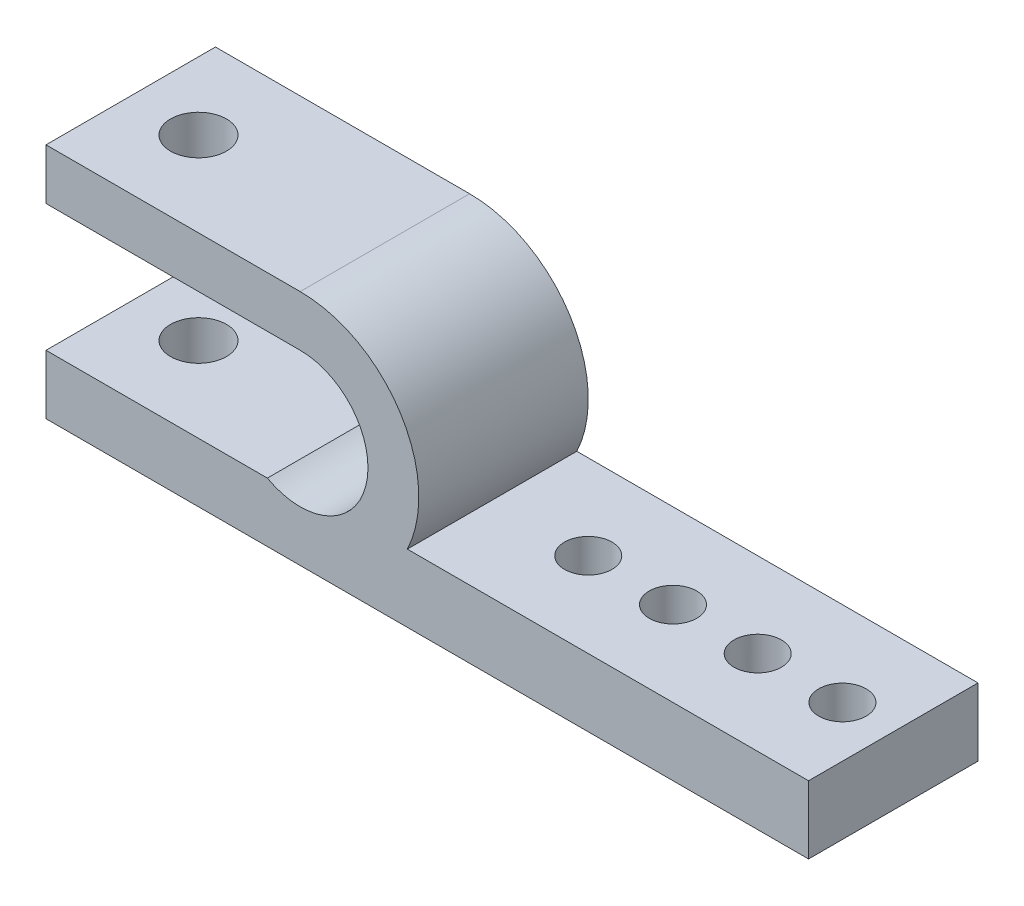
SolidWorks part; units mm, degrees
ref_plane "Front Plane" through (0, 0, 0) normal (0, 0, 1) x (1, 0, 0)
ref_plane "Top Plane" through (0, 0, 0) normal (0, 1, 0) x (1, 0, 0)
ref_plane "Right Plane" through (0, 0, 0) normal (1, 0, 0) x (0, 0, -1)
sketch "Sketch1" plane through (0, 0, 0) normal (0, 0, 1) x (1, 0, 0)
  line L0 (11.6797, 24.1068) -> (-3.3203, 24.1068)
  line L1 (9.7432, 16.6068) -> (-3.3203, 16.6068)
  line L2 (11.6797, 13.1068) -> (-3.3203, 13.1068)
  line L3 (-3.3203, 13.1068) -> (-3.3203, 16.6068)
  line L4 (11.6797, 27.1068) -> (-3.3203, 27.1068)
  line L5 (-3.3203, 27.1068) -> (-3.3203, 24.1068)
  circle A1 centre (27.6472, 16.9489) radius 1.65 construction
  arc A2 (11.6797, 13.1068) -> (11.6797, 27.1068) centre (11.6797, 20.1068) ccw
  circle A3 centre (27.6472, 16.9489) radius 1.65
  arc A4 (9.7432, 16.6068) -> (11.6797, 24.1068) centre (11.6797, 20.1068) ccw
  circle A5 centre (11.6797, 20.1068) radius 4 construction
  dimension "D1" = 8
  dimension "D2" = 14
  dimension "D4" = 15
  dimension "D3" = 7.5
  dimension "D5" = 15
extrude "Boss-Extrude1" add sketch "Sketch1" along normal blind 10 contours L4 L5 L0 A4 L1 L3 L2 A2
sketch "Sketch2" plane through (0, 27.1068, 0) normal (0, 1, 0) x (1, 0, 0)
  line L0 (-3.3203, -10) -> (-3.3203, 0) construction
  circle A0 centre (0.6797, -5) radius 1.65
  dimension "D1" = 3.3
  dimension "D2" = 4
extrude "Cut-Extrude1" cut sketch "Sketch2" against normal through all
ref_plane "Plane1" through (40.6472, 13.9489, 10) normal (1, 0, 0) x (0, 0, -1)
sketch "Sketch5" plane through (0, 0, 10) normal (0, 0, 1) x (1, 0, 0)
  line L0 (9.7432, 16.6068) -> (-3.3203, 16.6068) construction
  line L1 (41.6797, 17.1068) -> (14.3254, 17.1068)
  line L2 (41.6797, 17.1068) -> (41.6797, 13.1068)
  line L3 (41.6797, 13.1068) -> (-3.3203, 13.1068)
  line L4 (-3.3203, 13.1068) -> (-3.3203, 16.6068) construction
  line L5 (9.7432, 16.6068) -> (-3.3203, 16.6068)
  line L6 (-3.3203, 13.1068) -> (-3.3203, 16.6068)
  arc A0 (9.7432, 16.6068) -> (11.6797, 24.1068) centre (11.6797, 20.1068) ccw construction
  arc A1 (9.7432, 16.6068) -> (14.3254, 17.1068) centre (11.6797, 20.1068) ccw
  dimension "D1" = 45
extrude "Boss-Extrude2" add sketch "Sketch5" against normal blind 10 contours L2 L3 L6 L5 A1 L1
sketch "Sketch6" plane through (0, 13.1068, 0) normal (0, 1, 0) x (1, 0, 0)
  circle A1 centre (0.6797, -5) radius 1.65
  circle A2 centre (0.6797, -5) radius 1.65
  dimension "D1" = 0
sketch "Sketch8" plane through (0, 13.9489, 0) normal (0, 1, 0) x (1, 0, 0)
  line L1 (41.6797, -10) -> (18.0042, -10) construction
  line L2 (-3.3203, -10) -> (-3.3203, 0) construction
  circle A1 centre (28.6797, -5) radius 1.4
  circle A3 centre (38.6797, -5) radius 1.4
  circle A4 centre (23.6797, -5) radius 1.4
  circle A5 centre (33.6797, -5) radius 1.4
  dimension "D1" = 2.8
  dimension "D2" = 2.8
  dimension "D3" = 5
  dimension "D4" = 27
  dimension "D5" = 10
  dimension "D6" = 2.8
  dimension "D7" = 2.8
  dimension "D8" = 10
  dimension "D9" = 5
extrude "Cut-Extrude3" cut sketch "Sketch8" against normal blind 10 and the other way blind 10 contours A4 | A5 | A1 | A3
sketch "Sketch9" plane through (0, 27.1068, 0) normal (0, 1, 0) x (1, 0, 0)
  circle A0 centre (0.6797, -5) radius 1.65 construction
  circle A1 centre (0.6797, -5) radius 1.65
extrude "Cut-Extrude4" cut sketch "Sketch9" against normal through all
